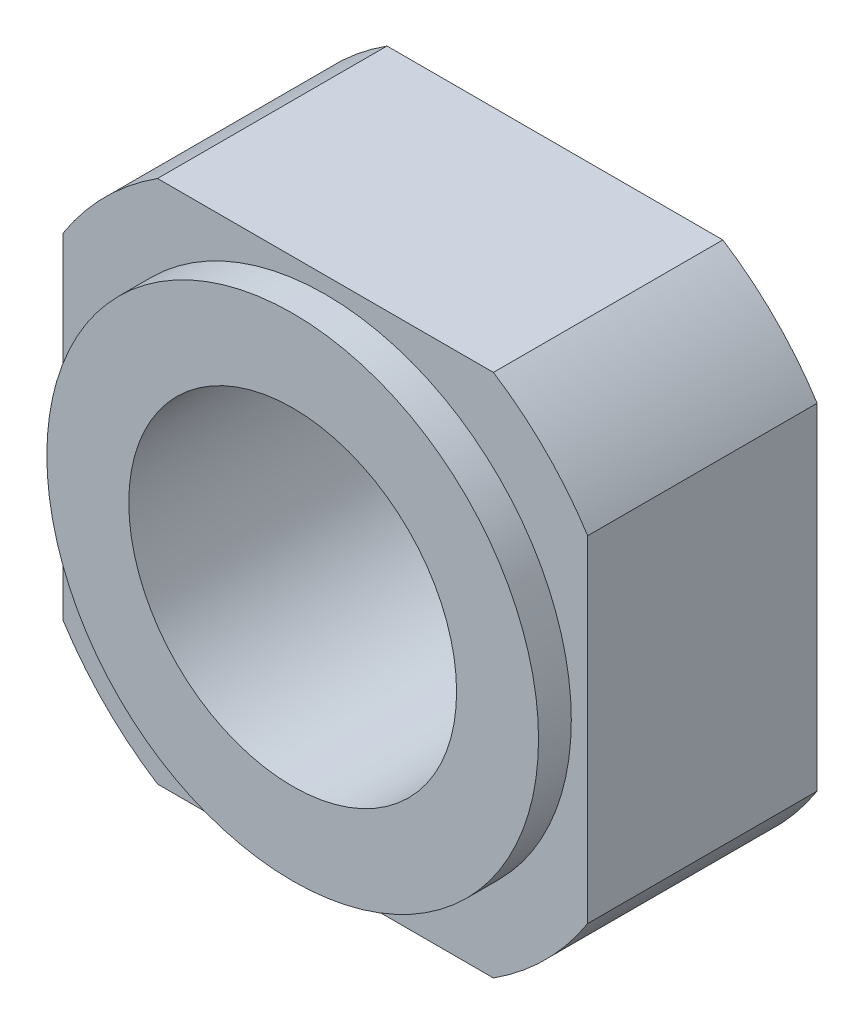
SolidWorks part; units mm, degrees
ref_plane "Ebene vorne" through (0, 0, 0) normal (0, 0, 1) x (1, 0, 0)
ref_plane "Ebene oben" through (0, 0, 0) normal (0, 1, 0) x (1, 0, 0)
ref_plane "Ebene rechts" through (0, 0, 0) normal (1, 0, 0) x (0, 0, -1)
sketch "Skizze1" plane through (0, 0, 0) normal (0, 0, 1) x (1, 0, 0)
  circle A0 centre (0, 0) radius 9.5
  circle A1 centre (0, 0) radius 5
  dimension "D1" = 19
  dimension "D2" = 10
extrude "Aufsatz-Linear austragen1" add sketch "Skizze1" along normal blind 8
sketch "Skizze2" plane through (0, 0, 0) normal (0, 0, -1) x (-1, 0, 0)
  line L1 (-8, -8) -> (8, -8)
  line L2 (-8, -8) -> (-8, 8)
  line L3 (-8, 8) -> (8, 8)
  line L4 (8, -8) -> (8, 8)
  line L5 (-8, -8) -> (8, 8) construction
  line L6 (-8, 8) -> (8, -8) construction
  point P0 (0, 0)
  dimension "D1" = 16
  dimension "D2" = 16
extrude "Schnitt-Linear austragen1" cut sketch "Skizze2" against normal blind 28 flip side to cut
sketch "Skizze3" plane through (0, 0, 8) normal (0, 0, 1) x (1, 0, 0)
  circle A0 centre (0, 0) radius 7.5
  dimension "D1" = 15
extrude "Schnitt-Linear austragen2" cut sketch "Skizze3" against normal blind 1 flip side to cut
